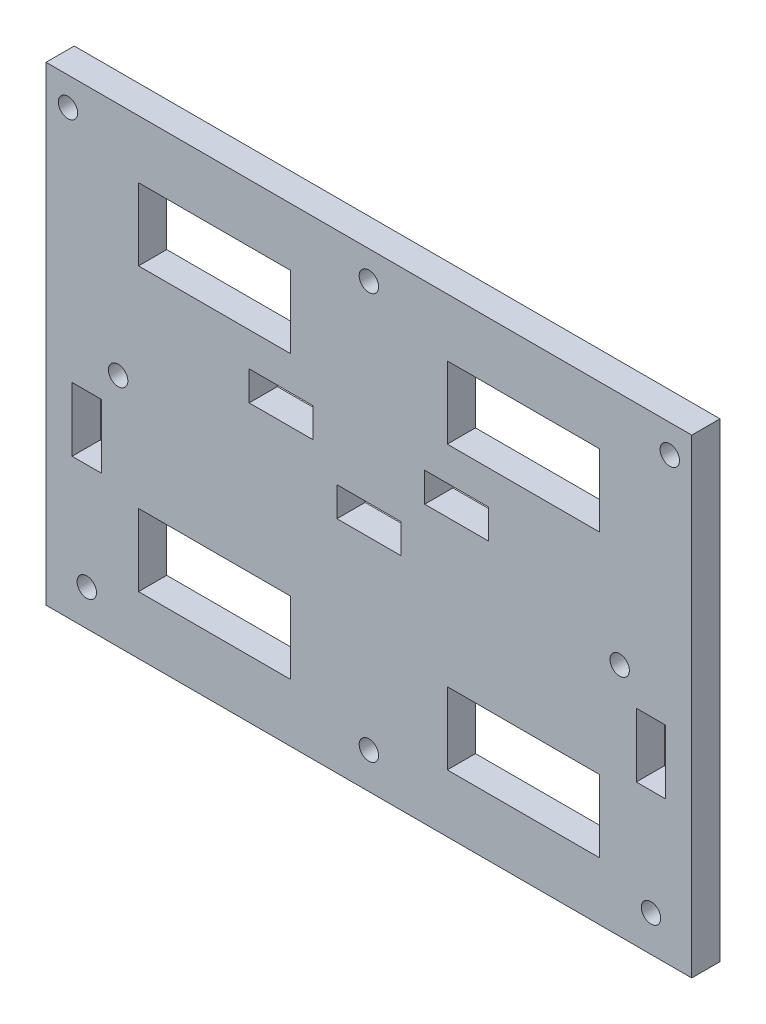
SolidWorks part; units mm, degrees
ref_plane "Front Plane" through (0, 0, 0) normal (0, 0, 1) x (1, 0, 0)
ref_plane "Top Plane" through (0, 0, 0) normal (0, 1, 0) x (1, 0, 0)
ref_plane "Right Plane" through (0, 0, 0) normal (1, 0, 0) x (0, 0, -1)
sketch "Sketch1" plane through (0, 0, 0) normal (0, 0, 1) x (1, 0, 0)
  line L0 (0, -37.5) -> (0, 37.5) construction
  line L1 (-51.5, -37.5) -> (51.5, -37.5)
  line L2 (-51.5, -37.5) -> (-51.5, 37.5)
  line L3 (-51.5, 37.5) -> (51.5, 37.5)
  line L4 (51.5, -37.5) -> (51.5, 37.5)
  line L5 (-51.5, -37.5) -> (51.5, 37.5) construction
  line L6 (-51.5, 37.5) -> (51.5, -37.5) construction
  line L7 (-51.5, 0) -> (51.5, 0) construction
  line L8 (-51.5, 22.5) -> (51.5, 22.5) construction
  line L9 (36.75, 16.75) -> (12.5, 28.25) construction
  line L10 (-36.75, 28.25) -> (-12.5, 28.25)
  line L11 (-36.75, 28.25) -> (-36.75, 16.75)
  line L12 (-36.75, 16.75) -> (-12.5, 16.75)
  line L13 (-12.5, 28.25) -> (-12.5, 16.75)
  line L14 (-36.75, 28.25) -> (-12.5, 16.75) construction
  line L15 (-36.75, 16.75) -> (-12.5, 28.25) construction
  line L16 (36.75, 28.25) -> (12.5, 16.75) construction
  line L17 (12.5, 28.25) -> (12.5, 16.75)
  line L18 (36.75, 16.75) -> (12.5, 16.75)
  line L19 (36.75, 28.25) -> (36.75, 16.75)
  line L20 (36.75, 28.25) -> (12.5, 28.25)
  line L21 (36.75, -28.25) -> (12.5, -16.75) construction
  line L22 (-36.75, -16.75) -> (-12.5, -28.25) construction
  line L23 (-36.75, -28.25) -> (-12.5, -16.75) construction
  line L24 (36.75, -16.75) -> (12.5, -28.25) construction
  line L25 (36.75, -28.25) -> (12.5, -28.25)
  line L26 (36.75, -28.25) -> (36.75, -16.75)
  line L27 (36.75, -16.75) -> (12.5, -16.75)
  line L28 (12.5, -28.25) -> (12.5, -16.75)
  line L29 (-12.5, -28.25) -> (-12.5, -16.75)
  line L30 (-36.75, -16.75) -> (-12.5, -16.75)
  line L31 (-36.75, -28.25) -> (-36.75, -16.75)
  line L32 (-36.75, -28.25) -> (-12.5, -28.25)
  point P0 (0, 0)
  point P12 (-24.625, 22.5)
  point P21 (24.625, 22.5)
  point P30 (24.625, -22.5)
  point P31 (-24.625, -22.5)
  dimension "D1" = 103
  dimension "D2" = 75
  dimension "D3" = 22.5
  dimension "D4" = 24.25
  dimension "D5" = 11.5
  dimension "D6" = 12.5
extrude "Boss-Extrude1" add sketch "Sketch1" along normal blind 4.5
sketch "Sketch2" plane through (0, 0, 4.5) normal (0, 0, 1) x (1, 0, 0)
  line L0 (0, -37.5) -> (0, 37.5) construction
  line L1 (-51.5, -37.5) -> (51.5, -37.5) construction
  line L2 (51.5, 37.5) -> (-51.5, 37.5) construction
  line L3 (-51.5, 0) -> (51.5, 0) construction
  line L4 (-51.5, 37.5) -> (-51.5, -37.5) construction
  line L5 (51.5, -37.5) -> (51.5, 37.5) construction
  line L6 (-40, 0) -> (40, 0) construction
  line L7 (-48, 33) -> (48, 33) construction
  circle A0 centre (-48, 33) radius 1.55
  circle A1 centre (48, 33) radius 1.55
  circle A2 centre (40, 0) radius 1.55
  circle A3 centre (-40, 0) radius 1.55
  circle A4 centre (0, 33) radius 1.55
  dimension "D1" = 3.1
  dimension "D7" = 3.1
  dimension "D8" = 3.1
  dimension "D9" = 3.1
  dimension "D2" = 48
  dimension "D3" = 33
  dimension "D4" = 80
  dimension "D5" = 40
  dimension "D6" = 0
extrude "screwHoles" cut sketch "Sketch2" against normal through all
sketch "Sketch3" plane through (0, 0, 4.5) normal (0, 0, 1) x (1, 0, 0)
  line L0 (-51.5, 9) -> (26.0486, 9) construction
  line L1 (-51.5, 37.5) -> (-51.5, -37.5) construction
  line L3 (0, 37.5) -> (0, -37.5) construction
  line L4 (51.5, 37.5) -> (-51.5, 37.5) construction
  line L5 (-51.5, -37.5) -> (51.5, -37.5) construction
  line L6 (19.1, 6.65) -> (8.9, 11.35) construction
  line L7 (-19.1, 11.35) -> (-8.9, 11.35)
  line L8 (-19.1, 11.35) -> (-19.1, 6.65)
  line L9 (-19.1, 6.65) -> (-8.9, 6.65)
  line L10 (-8.9, 11.35) -> (-8.9, 6.65)
  line L11 (-19.1, 11.35) -> (-8.9, 6.65) construction
  line L12 (-19.1, 6.65) -> (-8.9, 11.35) construction
  line L13 (19.1, 11.35) -> (8.9, 6.65) construction
  line L14 (8.9, 11.35) -> (8.9, 6.65)
  line L15 (19.1, 6.65) -> (8.9, 6.65)
  line L16 (19.1, 11.35) -> (19.1, 6.65)
  line L17 (19.1, 11.35) -> (8.9, 11.35)
  line L18 (-51.5, 37.5) -> (-51.5, -37.5) construction
  point P2 (-51.5, 0)
  point P12 (-14, 9)
  point P21 (14, 9)
  dimension "D1" = 10.2
  dimension "D2" = 4.7
  dimension "D3" = 14
  dimension "D4" = 9
extrude "BeltClamp" cut sketch "Sketch3" against normal through all
sketch "Sketch4" plane through (0, 0, 4.5) normal (0, 0, 1) x (1, 0, 0)
  line L0 (-51.5, 0) -> (51.5, 0) construction
  line L1 (-51.5, 37.5) -> (-51.5, -37.5) construction
  line L2 (51.5, -37.5) -> (51.5, 37.5) construction
  line L4 (-5.1, 2.35) -> (5.1, 2.35)
  line L5 (-5.1, 2.35) -> (-5.1, -2.35)
  line L6 (-5.1, -2.35) -> (5.1, -2.35)
  line L7 (5.1, 2.35) -> (5.1, -2.35)
  line L8 (-5.1, 2.35) -> (5.1, -2.35) construction
  line L9 (-5.1, -2.35) -> (5.1, 2.35) construction
  circle A0 centre (-40, 0) radius 1.55 construction
  point P6 (0, 0)
  dimension "D1" = 10.2
  dimension "D2" = 4.7
  dimension "D3" = 0
extrude "Cut-Extrude3" cut sketch "Sketch4" against normal through all
sketch "Sketch5" plane through (0, 0, 4.5) normal (0, 0, 1) x (1, 0, 0)
  line L0 (-51.5, -9.75) -> (51.5, -9.75) construction
  line L1 (-51.5, 37.5) -> (-51.5, -37.5) construction
  line L2 (51.5, -37.5) -> (51.5, 37.5) construction
  line L3 (5.1, -2.35) -> (5.1, 2.35) construction
  line L4 (0, -37.5) -> (0, 37.5) construction
  line L5 (-51.5, -37.5) -> (51.5, -37.5) construction
  line L6 (51.5, 37.5) -> (-51.5, 37.5) construction
  line L7 (-42.65, -14.85) -> (-47.35, -4.65) construction
  line L8 (42.65, -4.65) -> (47.35, -4.65)
  line L9 (42.65, -4.65) -> (42.65, -14.85)
  line L10 (42.65, -14.85) -> (47.35, -14.85)
  line L11 (47.35, -4.65) -> (47.35, -14.85)
  line L12 (42.65, -4.65) -> (47.35, -14.85) construction
  line L13 (42.65, -14.85) -> (47.35, -4.65) construction
  line L14 (-42.65, -4.65) -> (-47.35, -14.85) construction
  line L15 (-47.35, -4.65) -> (-47.35, -14.85)
  line L16 (-42.65, -14.85) -> (-47.35, -14.85)
  line L17 (-42.65, -4.65) -> (-42.65, -14.85)
  line L18 (-42.65, -4.65) -> (-47.35, -4.65)
  line L19 (45, -9.75) -> (45, -37.5) construction
  line L20 (-45, -9.75) -> (-45, -37.5) construction
  line L21 (-45, -31.75) -> (45, -31.75) construction
  circle A0 centre (45, -31.75) radius 1.55
  circle A1 centre (-45, -31.75) radius 1.55
  circle A2 centre (0, -31.75) radius 1.55
  point P6 (5.1, 0)
  point P15 (45, -9.75)
  point P24 (-45, -9.75)
  dimension "D7" = 3.1
  dimension "D5" = 3.1
  dimension "D1" = 9.75
  dimension "D2" = 10.2
  dimension "D3" = 4.7
  dimension "D4" = 45
  dimension "D6" = 22
extrude "Cut-Extrude4" cut sketch "Sketch5" against normal through all
sketch "Sketch6" plane through (0, 0, 4.5) normal (0, 0, 1) x (1, 0, 0)
  line L0 (-47.35, -9.75) -> (47.35, -9.75) construction
  line L1 (-47.35, -4.65) -> (-47.35, -14.85) construction
  line L2 (47.35, -14.85) -> (47.35, -4.65) construction
  line L3 (0, -2.35) -> (0, -37.5) construction
  line L4 (-5.1, -2.35) -> (5.1, -2.35) construction
  line L5 (-51.5, -37.5) -> (51.5, -37.5) construction
  line L6 (45, -14.85) -> (45, -4.65) construction
  line L7 (42.65, -14.85) -> (47.35, -14.85) construction
  line L8 (47.35, -4.65) -> (42.65, -4.65) construction
  line L9 (42.65, -4.65) -> (42.65, -14.85) construction
  line L10 (41.65, -15.85) -> (48.35, -15.85)
  line L11 (41.65, -15.85) -> (41.65, -3.65)
  line L12 (41.65, -3.65) -> (48.35, -3.65)
  line L13 (48.35, -15.85) -> (48.35, -3.65)
  line L14 (41.65, -15.85) -> (48.35, -3.65) construction
  line L15 (41.65, -3.65) -> (48.35, -15.85) construction
  line L16 (-41.65, -3.65) -> (-48.35, -15.85) construction
  line L17 (-41.65, -15.85) -> (-48.35, -3.65) construction
  line L18 (-45, -14.85) -> (-45, -4.65) construction
  line L19 (-48.35, -15.85) -> (-48.35, -3.65)
  line L20 (-41.65, -3.65) -> (-48.35, -3.65)
  line L21 (-41.65, -15.85) -> (-41.65, -3.65)
  line L22 (-41.65, -15.85) -> (-48.35, -15.85)
  circle A0 centre (45, -9.75) radius 1.55
  circle A1 centre (-45, -9.75) radius 1.55
  point P18 (45, -9.75)
  dimension "D3" = 3.1
  dimension "D1" = 1
  dimension "D2" = 1
extrude "FrontToRear1" [suppressed] add sketch "Sketch6" against normal up to surface (4.5 mm away)
sketch "Sketch7" plane through (0, 0, 4.5) normal (0, 0, 1) x (1, 0, 0)
  line L0 (5.1, 2.35) -> (-5.1, 2.35) construction
  line L1 (-45, -3.35) -> (45, -3.35)
  line L2 (-45, -3.35) -> (-45, 3.35)
  line L3 (-45, 3.35) -> (45, 3.35)
  line L4 (45, -3.35) -> (45, 3.35)
  line L5 (-45, -3.35) -> (45, 3.35) construction
  line L6 (-45, 3.35) -> (45, -3.35) construction
  circle A0 centre (40, 0) radius 1.55 construction
  point P0 (0, 0)
  dimension "D1" = 1
  dimension "D2" = 5
extrude "FrontToRear2" [suppressed] add sketch "Sketch7" against normal through all
equation "\"X-ROD-SPACING\"=45"
equation "\"Y-ROD-SPACING\"=75"
equation "\"Z-ROD-SPACING\"=17.5"
equation "\"Y-BED-OFFSET\"=2"
equation "\"Y-BED-ROD-INSET\"=3.5"
equation "\"Y-BED-SCREW-SPACING\"=209"
equation "\"Y-BED-SCREW-CUTOUT-SLOT-HEIGHT\"=1"
equation "\"T-SLOT-NUT-FILLET-RADIUS\"=0.25"
equation "\"T-SLOT-SCREW-SHAFT-RADIUS\"=1.75"
equation "\"T-SLOT-SCREW-SHAFT-CUTOUT-LENGTH\"=10.5"
equation "\"T-SLOT-NUT-DEPTH\"=4.2"
equation "\"T-SLOT-NUT-WIDTH\"=3"
equation "\"T-SLOT-NUT-END-DISTANCE\"=8"
equation "\"ACRYLIC-THICKNESS\"=10"
equation "\"ACRYLIC-THICKNESS2\"=4.5"
equation "\"ACRYLIC-TAB-CUTOUT-SIZE\"=\"ACRYLIC-THICKNESS\"+\"ACRYLIC-TAB-TOLERANCE\"*2"
equation "\"ACRYLIC-TAB-WIDTH\"=\"ACRYLIC-THICKNESS\""
equation "\"ACRYLIC-M3-HOLE\"=3.1"
equation "\"SMOOTHROD-CAP-SCREW-DISTANCE\"=20"
equation "\"FRAME-WIDTH-INNER\"=370"
equation "\"NEMA17-HOLE-SPACING\"=31"
equation "\"NEMA17-CENTRAL-CUTOUT\"=22.5"
equation "\"Z-BRACKET-REACH\"=55"
equation "\"Z-ROD-INSET\"=16"
equation "\"TOP-BRACKET-SPACING\"=40"
equation "\"SMOOTHROD-X-LENGTH\"=350"
equation "\"SMOOTHROD-Y-LENGTH\"=350"
equation "\"SMOOTHROD-Z-LENGTH\"=350"
equation "\"SMOOTHROD-TIGHTENING-HEADROOM\"=1"
equation "\"LEADSCREW-Z-LENGTH\"=300"
equation "\"SCREW-LENGTH-FRAME\"=\"ACRYLIC-THICKNESS\" + 10"
equation "\"SCREW-LENGTH-MOTOR\"=\"ACRYLIC-THICKNESS\" + 5"
equation "\"SCREW-HEAD-RADIUS\"=6"
equation "\"PRINTED-X-SMOOTHROD-DIAMETER\"=8.2"
equation "\"PRINTED-X-SMOOTHROD-CUTOUT\"=10"
equation "\"PRINTED-X-BASE-HEIGHT\"=10"
equation "\"PRINTED-LM8UU-CUTOUT-SIZE\"=15.25"
equation "\"PRINTED-LM8UU-CUTOUT-LENGTH\"=24.5"
equation "\"PRINTED-X-IDLER-HEIGHT\"=16"
equation "\"PSU-MOUNTING-WIDTH\"=95"
equation "\"PSU-MOUNTING-HEIGHT\"=177"
equation "\"Y-BELT-TO-ROD-DISTANCE\"=20"
equation "\"SPOOL-HOLDER-ROD-SPACING\"=150"
equation "\"D3@Sketch1\"=\"X-ROD-SPACING\"/2"
equation "\"D4@Sketch1\"=\"ACRYLIC-X-CARRIAGE-LM8UU-CUTOUT-WIDTH\""
equation "\"D1@Boss-Extrude1\"=\"ACRYLIC-THICKNESS2\""
equation "\"D1@Sketch2\"=\"ACRYLIC-M3-HOLE\""
equation "\"D1@Sketch3\"=\"ACRYLIC-TAB-CUTOUT-SIZE\""
equation "\"D2@Sketch3\"=\"ACRYLIC-THICKNESS2\"+\"ACRYLIC-TAB-TOLERANCE\"*2"
equation "\"ACRYLIC-X-CARRIAGE-WIDTH\"=55"
equation "\"ACRYLIC-X-CARRIAGE-HEIGHT\"=75"
equation "\"D2@Sketch1\"=\"ACRYLIC-X-CARRIAGE-HEIGHT\""
equation "\"ACRYLIC-X-CARRIAGE-CENTER-TAB-SPACING\"=14"
equation "\"D3@Sketch3\"=\"ACRYLIC-X-CARRIAGE-CENTER-TAB-SPACING\""
equation "\"SCREW-LENGTH-EXTRUDER\"=28"
equation "\"ACRYLIC-X-CARRIAGE-SCREW-SPACING-X\"=15"
equation "\"ACRYLIC-X-CARRIAGE-SCREW-SPACING-Y\"=33"
equation "\"D3@Sketch2\"=\"ACRYLIC-X-CARRIAGE-SCREW-SPACING-Y\""
equation "\"D1@Sketch4\"=\"ACRYLIC-TAB-CUTOUT-SIZE\""
equation "\"D2@Sketch4\"=\"ACRYLIC-THICKNESS2\"+\"ACRYLIC-TAB-TOLERANCE\"*2"
equation "\"D2@Sketch5\"=\"ACRYLIC-TAB-CUTOUT-SIZE\""
equation "\"D3@Sketch5\"=\"ACRYLIC-THICKNESS2\"+\"ACRYLIC-TAB-TOLERANCE\"*2"
equation "\"ACRYLIC-X-CARRIAGE-EXTRUDER-SHELF-DEPTH\"=\"ACRYLIC-X-CARRIAGE-EXTRUDER-OFFSET\" + 30"
equation "\"ACRYLIC-X-CARRIAGE-EXTRUDER-BRACE-SPACING\"=23"
equation "\"D4@Sketch5\"=\"ACRYLIC-X-CARRIAGE-DUAL-MOUNT-BRACE-WIDTH\""
equation "\"D1@Sketch5\"=\"ACRYLIC-THICKNESS2\"/2 + 7.5"
equation "\"D4@Sketch2\"=\"ACRYLIC-X-CARRIAGE-DUAL-MOUNT-SCREW-WIDTH\"*2"
equation "\"D5@Sketch2\"=\"ACRYLIC-X-CARRIAGE-DUAL-MOUNT-SCREW-WIDTH\""
equation "\"D7@Sketch2\"=\"ACRYLIC-M3-HOLE\""
equation "\"D8@Sketch2\"=\"ACRYLIC-M3-HOLE\""
equation "\"ACRYLIC-X-CARRIAGE-LM8UU-CUTOUT-WIDTH\"=24.25"
equation "\"ACRYLIC-TAB-TOLERANCE\"=.1"
equation "\"ACRYLIC-X-CARRIAGE-EXTRUDER-OFFSET\"=26"
equation "\"ACRYLIC-X-CARRIAGE-EXTRUDER-ANGLE\"=90"
equation "\"ACRYLIC-X-CARRIAGE-EXTRUDER-BRACE-TAB-OFFSET\"=20"
equation "\"ACRYLIC-X-CARRIAGE-EXTRUDER-BRACE-HEIGHT\"=35"
equation "\"ACRYLIC-X-CARRIAGE-EXTRUDER-BRACE-SCREW-SPACING\"=22"
equation "\"D5@Sketch5\"=\"ACRYLIC-M3-HOLE\""
equation "\"D3@Sketch6\"=\"ACRYLIC-M3-HOLE\""
equation "\"ACRYLIC-X-CARRIAGE-DUAL-WIDTH-MULTIPLIER\"=1.65"
equation "\"ACRYLIC-X-CARRIAGE-DUAL-HOTEND-SPACING\"=42"
equation "\"ACRYLIC-X-CARRIAGE-DUAL-WIDTH\"=103"
equation "\"ACRYLIC-X-CARRIAGE-DUAL-HOTEND-SEPARATION\"=35"
equation "\"ACRYLIC-X-CARRIAGE-DUAL-MOUNT-PLATE-DEPTH\"=76"
equation "\"ACRYLIC-X-CARRIAGE-DUAL-MOUNT-BRACE-WIDTH\"=45"
equation "\"ACRYLIC-X-CARRIAGE-DUAL-MOUNT-SCREW-WIDTH\"=40"
equation "\"D1@Sketch1\"=\"ACRYLIC-X-CARRIAGE-DUAL-WIDTH\""
equation "\"D9@Sketch2\"=\"ACRYLIC-M3-HOLE\""
equation "\"D7@Sketch5\"=\"ACRYLIC-M3-HOLE\""
equation "\"ACRYLIC-X-CARRIAGE-LM8UU-CUTOUT-HEIGHT\"=11.5"
equation "\"D5@Sketch1\"=\"ACRYLIC-X-CARRIAGE-LM8UU-CUTOUT-HEIGHT\""
